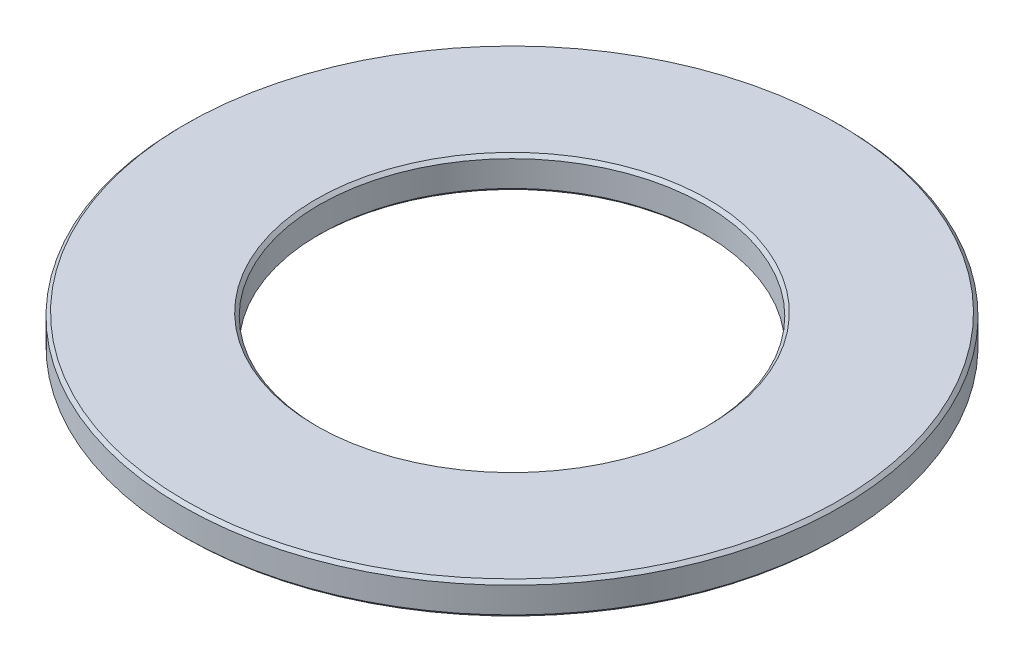
SolidWorks part; units mm, degrees
material "6061 Alloy"
ref_plane "Front Plane" through (0, 0, 0) normal (0, 0, 1) x (1, 0, 0)
ref_plane "Top Plane" through (0, 0, 0) normal (0, 1, 0) x (1, 0, 0)
ref_plane "Right Plane" through (0, 0, 0) normal (1, 0, 0) x (0, 0, -1)
sketch "ProfileS" plane through (0, 0, 0) normal (0, 1, 0) x (1, 0, 0)
  circle A0 centre (0, 0) radius 6
  circle A1 centre (0, 0) radius 10.25
  dimension "InnerDia" = 12
  dimension "RefDia" = 20.5
  dimension "DiaControl" = 4.25
extrude "Profile" add sketch "ProfileS" along normal blind 1
chamfer "OuterC" distance 0.1 angle 45 2 edges at (0, 0, 10.25) (0, 1, 10.25)
chamfer "InnerC" distance 0.1 2 edges at (0, 0, 6) (0, 1, 6)
